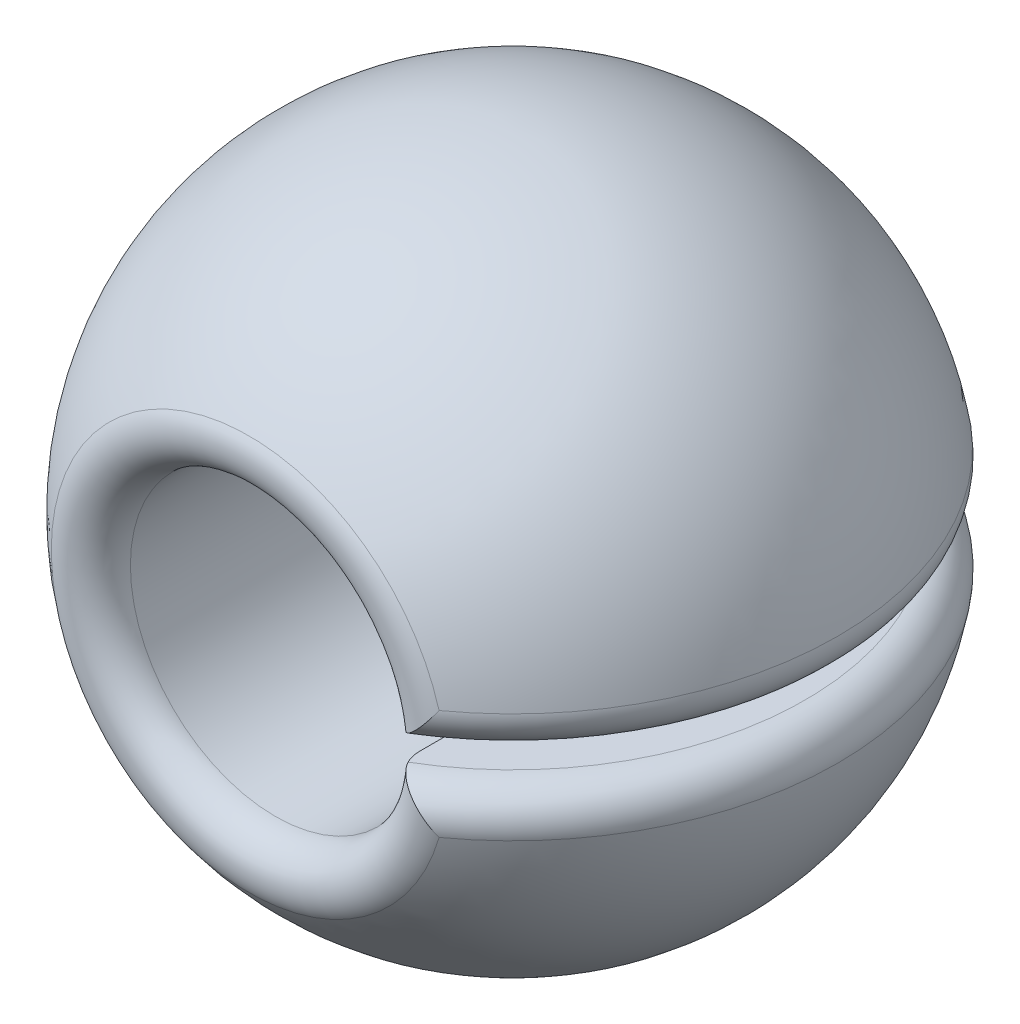
SolidWorks part; units mm, degrees
ref_plane "정면" through (0, 0, 0) normal (0, 0, 1) x (1, 0, 0)
ref_plane "윗면" through (0, 0, 0) normal (0, 1, 0) x (1, 0, 0)
ref_plane "우측면" through (0, 0, 0) normal (1, 0, 0) x (0, 0, -1)
sketch "스케치1" plane through (0, 0, 0) normal (0, 0, 1) x (1, 0, 0)
  line L0 (0, 11.7897) -> (0, -13.2661) construction
  line L1 (0, 10) -> (0, -10)
  arc A0 (0, 10) -> (0, -10) centre (0, 0) ccw
  dimension "D1" = 20
revolve "회전2" add sketch "스케치1" angle 360 about L0
sketch "스케치2" plane through (0, 0, 0) normal (0, 0, 1) x (1, 0, 0)
  circle A1 centre (0, 0) radius 4.4
  dimension "D1" = 8.8
extrude "컷-돌출1" cut sketch "스케치2" against normal mid plane 30 contours A1
sketch "스케치3" plane through (0, 0, 0) normal (0, 0, 1) x (1, 0, 0)
  line L1 (1.4366, 0.5) -> (11.8583, 0.5)
  line L2 (1.4366, 0.5) -> (1.4366, -0.5)
  line L3 (1.4366, -0.5) -> (11.8583, -0.5)
  line L4 (11.8583, 0.5) -> (11.8583, -0.5)
  point P4 (1.4366, 0)
  dimension "D1" = 1
extrude "컷-돌출2" cut sketch "스케치3" against normal mid plane 30
fillet "필렛1" radius 1 4 edges at (-4.4, 0, -8.98) (-4.4, 0, 8.98) (9.9875, -0.5, 0) (9.9875, 0.5, 0)
ref_point "점1"
